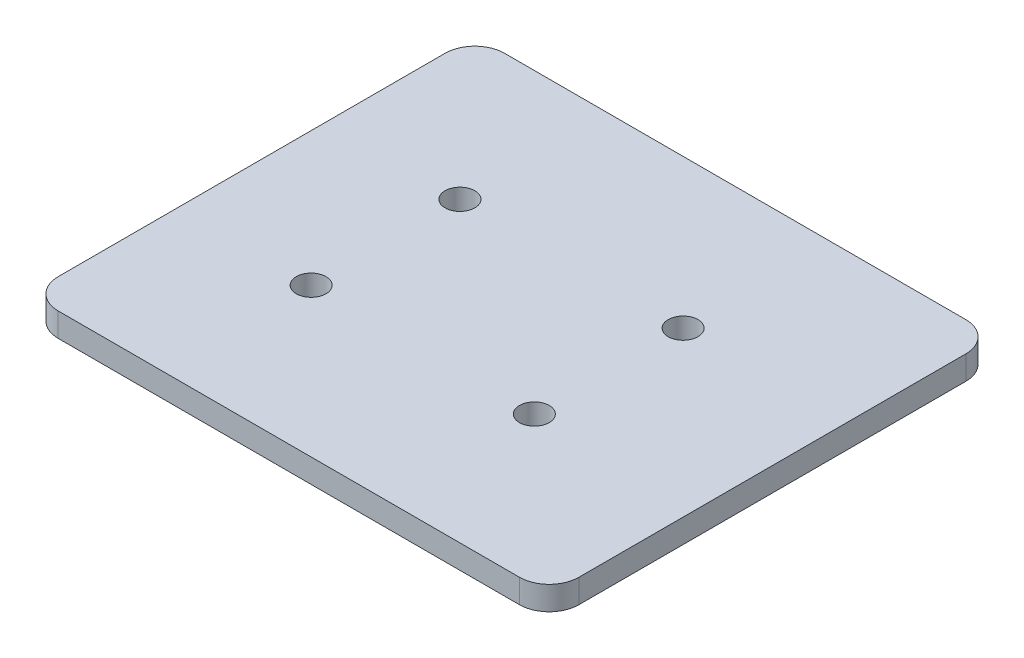
SolidWorks part; units mm, degrees
material "A-玻璃纤维"
ref_plane "前视基准面" through (0, 0, 0) normal (0, 0, 1) x (1, 0, 0)
ref_plane "上视基准面" through (0, 0, 0) normal (0, 1, 0) x (1, 0, 0)
ref_plane "右视基准面" through (0, 0, 0) normal (1, 0, 0) x (0, 0, -1)
other "Configuration Table"
sketch "草图1" plane through (0, 0, 0) normal (0, 1, 0) x (1, 0, 0)
  line L1 (-17.5, -15) -> (17.5, -15)
  line L2 (-17.5, -15) -> (-17.5, 15)
  line L3 (-17.5, 15) -> (17.5, 15)
  line L4 (17.5, -15) -> (17.5, 15)
  line L5 (-17.5, -15) -> (17.5, 15) construction
  line L6 (-17.5, 15) -> (17.5, -15) construction
  circle A3 centre (-8.5, 5) radius 1
  circle A4 centre (6.5, 5) radius 1
  circle A5 centre (-8.5, -5) radius 1
  circle A6 centre (6.5, -5) radius 1
  point P0 (0, 0)
  dimension "D3" = 2
  dimension "D4" = 2
  dimension "D5" = 2
  dimension "D6" = 2
  dimension "D7" = 9
  dimension "D8" = 10
  dimension "D9" = 10
  dimension "D10" = 15
  dimension "D11" = 10
  dimension "D12" = 10
  dimension "D13" = 15
  dimension "D14" = 9
  dimension "D1" = 35
  dimension "D2" = 30
extrude "凸台-拉伸1" add sketch "草图1" along normal blind 1.6
fillet "圆角1" radius 2 4 edges at (-17.5, 0.8, -15) (-17.5, 0.8, 15) (17.5, 0.8, -15) (17.5, 0.8, 15)
